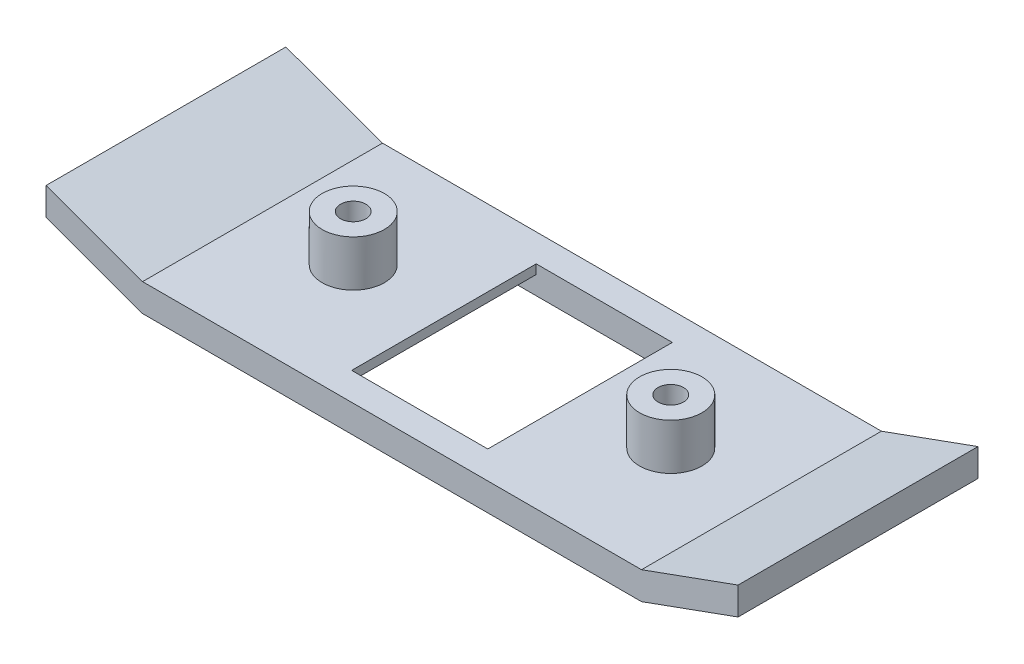
SolidWorks part; units mm, degrees
material "1060 Alloy"
ref_plane "Front Plane" through (0, 0, 0) normal (0, 0, 1) x (1, 0, 0)
ref_plane "Top Plane" through (0, 0, 0) normal (0, 1, 0) x (1, 0, 0)
ref_plane "Right Plane" through (0, 0, 0) normal (1, 0, 0) x (0, 0, -1)
sketch "Sketch1" plane through (0, 0, 0) normal (0, 0, 1) x (1, 0, 0)
  line L0 (0, 0) -> (0, 3) construction
  line L2 (27.0353, 0) -> (-27.0353, 0)
  line L4 (-27.0353, 0) -> (-37.5, 3.7906)
  line L6 (-37.5, 3.7906) -> (-37.5, 6.7906)
  line L7 (-37.5, 6.7906) -> (-27.0353, 3)
  line L9 (-27.0353, 3) -> (27.0353, 3)
  line L12 (-27.0353, 0) -> (-27.0353, 3) construction
  line L15 (27.0353, 0) -> (37.5, 3.7906)
  line L16 (37.5, 3.7906) -> (37.5, 6.7906)
  line L17 (37.5, 6.7906) -> (27.0353, 3)
  dimension "D1" = 3
extrude "Boss-Extrude1" add sketch "Sketch1" along normal offset from surface (26 mm away) 1
sketch "Sketch2" plane through (0, 0, 0) normal (0, -1, 0) x (1, 0, 0)
  line L1 (37.5, 23) -> (-37.5, 23)
  line L2 (37.5, 26) -> (37.5, 0) construction
  line L3 (7.375, 23) -> (37.5, 23) construction
  line L4 (-37.5, 26) -> (-37.5, 0) construction
  line L8 (-37.5, 23) -> (-7.375, 23) construction
  line L9 (-37.5, 23) -> (-37.5, 3)
  line L10 (-7.375, 3) -> (-37.5, 3) construction
  line L11 (-37.5, 3) -> (37.5, 3)
  line L12 (37.5, 3) -> (7.375, 3) construction
  line L13 (37.5, 3) -> (37.5, 23)
extrude "Cut-Extrude1" cut sketch "Sketch2" against normal blind 1
sketch "Sketch4" plane through (0, 1, 0) normal (0, -1, 0) x (1, 0, 0)
  line L0 (-37.5, 23) -> (37.5, 23)
  line L1 (-37.5, 26) -> (-37.5, 0) construction
  line L2 (-37.5, 23) -> (-7.375, 23) construction
  line L3 (7.375, 23) -> (37.5, 23) construction
  line L4 (37.5, 26) -> (37.5, 0) construction
  line L5 (37.5, 23) -> (37.5, 3)
  line L6 (37.5, 3) -> (-37.5, 3)
  line L7 (-7.375, 3) -> (-37.5, 3) construction
  line L8 (-37.5, 3) -> (-37.5, 23)
extrude "Cut-Extrude2" cut sketch "Sketch4" against normal blind 1
sketch "Sketch5" plane through (0, 2, 0) normal (0, -1, 0) x (1, 0, 0)
  line L0 (7.375, 23) -> (7.375, 3) construction
  line L1 (-7.375, 23) -> (7.375, 23) construction
  line L2 (-7.375, 3) -> (-7.375, 23) construction
  line L3 (7.375, 3) -> (-7.375, 3) construction
  line L4 (7.375, 23) -> (7.375, 3)
  line L5 (-7.375, 23) -> (7.375, 23)
  line L6 (-7.375, 3) -> (-7.375, 23)
  line L7 (7.375, 3) -> (-7.375, 3)
extrude "Cut-Extrude3" cut sketch "Sketch5" against normal through all
sketch "Sketch6" plane through (0, 3, 0) normal (0, 1, 0) x (1, 0, 0)
  line L0 (-27.0353, -13) -> (-7.375, -13) construction
  line L1 (-27.0353, -26) -> (-27.0353, 0) construction
  line L3 (0, 0) -> (0, -26) construction
  line L6 (-27.0353, -26) -> (27.0353, -26) construction
  line L7 (-7.375, -23) -> (-7.375, -3) construction
  circle A0 centre (-17.2051, -13) radius 1.375
  circle A3 centre (-17.2051, -13) radius 1.375 construction
  circle A4 centre (-17.2051, -13) radius 3.375
  circle A5 centre (17.2051, -13) radius 1.375
  circle A6 centre (17.2051, -13) radius 3.375
  dimension "D1" = 2
extrude "Boss-Extrude2" add sketch "Sketch6" along normal blind 5
